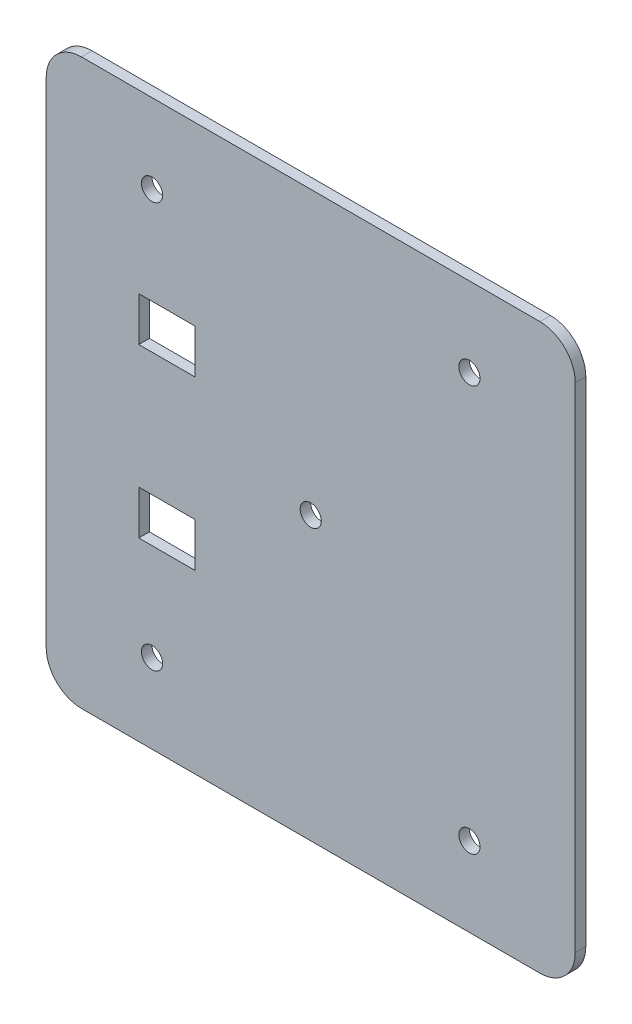
SolidWorks part; units mm, degrees
ref_plane "Front Plane" through (0, 0, 0) normal (0, 0, 1) x (1, 0, 0)
ref_plane "Top Plane" through (0, 0, 0) normal (0, 1, 0) x (1, 0, 0)
ref_plane "Right Plane" through (0, 0, 0) normal (1, 0, 0) x (0, 0, -1)
sketch "Sketch1" plane through (0, 0, 0) normal (0, 0, 1) x (1, 0, 0)
  line L0 (-22.5, -22.5) -> (22.5, -22.5) construction
  line L1 (22.5, -22.5) -> (22.5, 22.5) construction
  line L2 (22.5, 22.5) -> (-22.5, 22.5) construction
  line L3 (-22.5, 22.5) -> (-22.5, -22.5) construction
  line L4 (22.5, 92.5) -> (22.5, 137.5) construction
  line L5 (22.5, 137.5) -> (-22.5, 137.5) construction
  line L6 (-22.5, 137.5) -> (-22.5, 92.5) construction
  line L7 (-22.5, 92.5) -> (22.5, 92.5) construction
  line L8 (-22.5, -22.5) -> (22.5, -22.5)
  line L9 (22.5, -22.5) -> (22.5, 22.5)
  line L10 (22.5, 22.5) -> (-22.5, 22.5)
  line L11 (-22.5, 22.5) -> (-22.5, -22.5)
  line L12 (22.5, 92.5) -> (22.5, 137.5)
  line L13 (22.5, 137.5) -> (-22.5, 137.5)
  line L14 (-22.5, 137.5) -> (-22.5, 92.5)
  line L15 (-22.5, 92.5) -> (22.5, 92.5)
  line L16 (-22.5, 92.5) -> (22.5, 137.5)
  line L17 (-22.5, 137.5) -> (22.5, 92.5)
  line L18 (22.5, 22.5) -> (-22.5, -22.5)
  line L19 (-22.5, 22.5) -> (22.5, -22.5)
  line L20 (75, -102.5) -> (75, 57.5)
  line L21 (-55, -102.5) -> (75, -102.5)
  line L22 (-75, -82.5) -> (-75, 197.5)
  line L23 (75, -102.5) -> (75, 217.5)
  line L24 (-55, 217.5) -> (75, 217.5)
  line L25 (-75, -102.5) -> (75, 217.5) construction
  line L26 (75, -102.5) -> (-75, 217.5) construction
  line L27 (0, 0) -> (0, 57.5)
  line L28 (75, -102.5) -> (75, 217.5)
  line L29 (75, -102.5) -> (205, -102.5)
  line L30 (75, 217.5) -> (205, 217.5)
  line L31 (225, -82.5) -> (225, 197.5)
  line L32 (165, 217.5) -> (165, 172.5)
  line L33 (165, 172.5) -> (225, 172.5)
  line L34 (225, -57.5) -> (165, -57.5)
  line L35 (165, -57.5) -> (165, -102.5)
  line L36 (-15, -102.5) -> (-15, -57.5)
  line L37 (-15, -57.5) -> (-75, -57.5)
  line L38 (-75, 172.5) -> (-15, 172.5)
  line L39 (-15, 172.5) -> (-15, 217.5)
  line L40 (-22.5, 92.5) -> (9.5, 92.5)
  line L41 (-22.5, 92.5) -> (-22.5, 117.5)
  line L42 (9.5, 92.5) -> (9.5, 117.5)
  line L43 (-22.5, 117.5) -> (9.5, 117.5)
  line L44 (-22.5, 22.5) -> (9.5, 22.5)
  line L45 (-22.5, 22.5) -> (-22.5, -2.5)
  line L46 (9.5, 22.5) -> (9.5, -2.5)
  line L47 (-22.5, -2.5) -> (9.5, -2.5)
  circle A0 centre (-15, 172.5) radius 6
  circle A1 centre (165, 172.5) radius 6
  circle A2 centre (165, -57.5) radius 6
  circle A3 centre (-15, -57.5) radius 6
  circle A4 centre (75, 57.5) radius 6
  arc A5 (-75, -82.5) -> (-55, -102.5) centre (-55, -82.5) ccw
  arc A6 (205, -102.5) -> (225, -82.5) centre (205, -82.5) ccw
  arc A7 (205, 217.5) -> (225, 197.5) centre (205, 197.5) cw
  arc A8 (-75, 197.5) -> (-55, 217.5) centre (-55, 197.5) cw
  point P7 (0, 57.5)
  point P43 (225, 217.5)
  dimension "D7" = 12
  dimension "D8" = 160
  dimension "D9" = 20
  dimension "D1" = 150
  dimension "D2" = 320
  dimension "D3" = 57.5
  dimension "D4" = 150
  dimension "D5" = 60
  dimension "D6" = 45
  dimension "D10" = 45
  dimension "D11" = 25
  dimension "D12" = 25
  dimension "D13" = 32
extrude "Boss-Extrude1" add sketch "Sketch1" along normal blind 6
